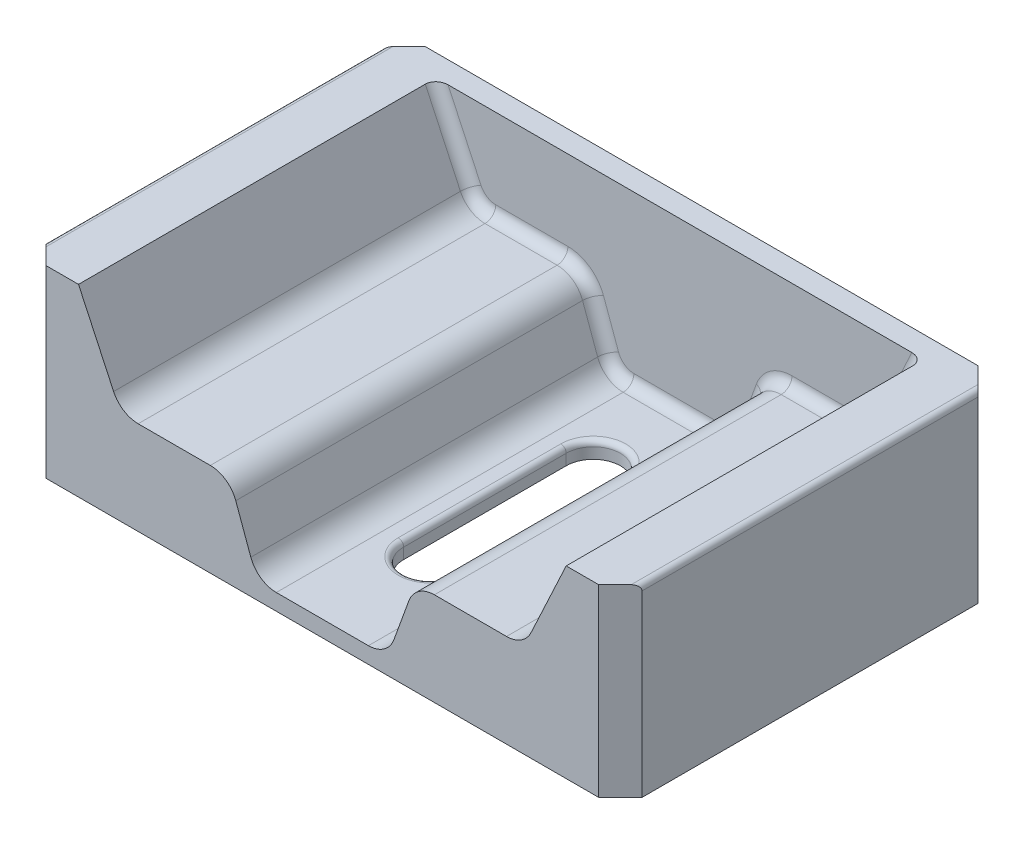
SolidWorks part; units mm, degrees
ref_plane "Front Plane" through (0, 0, 0) normal (0, 0, 1) x (1, 0, 0)
ref_plane "Top Plane" through (0, 0, 0) normal (0, 1, 0) x (1, 0, 0)
ref_plane "Right Plane" through (0, 0, 0) normal (1, 0, 0) x (0, 0, -1)
sketch "Sketch3" plane through (0, 0, 0) normal (0, 1, 0) x (1, 0, 0)
  line L1 (-69.85, -44.45) -> (69.85, -44.45)
  line L2 (-69.85, -44.45) -> (-69.85, 44.45)
  line L3 (-69.85, 44.45) -> (69.85, 44.45)
  line L4 (69.85, -44.45) -> (69.85, 44.45)
  line L5 (-69.85, -44.45) -> (69.85, 44.45) construction
  line L6 (-69.85, 44.45) -> (69.85, -44.45) construction
  point P0 (0, 0)
  dimension "D1" = 139.7
  dimension "D2" = 88.9
extrude "Boss-Extrude2" add sketch "Sketch3" along normal blind 43.18
sketch "Sketch4" plane through (0, 0, 44.45) normal (0, 0, 1) x (1, 0, 0)
  line L0 (-57.15, 43.18) -> (57.15, 43.18)
  line L1 (-69.85, 43.18) -> (69.85, 43.18) construction
  line L2 (57.15, 43.18) -> (47.2144, 21.8731)
  line L3 (47.2144, 21.8731) -> (21.8144, 21.8731)
  line L4 (21.8144, 21.8731) -> (15.24, 3.81)
  line L5 (15.24, 3.81) -> (-15.24, 3.81)
  line L6 (-15.24, 3.81) -> (-21.8144, 21.8731)
  line L7 (-21.8144, 21.8731) -> (-47.2144, 21.8731)
  line L8 (-47.2144, 21.8731) -> (-57.15, 43.18)
  line L9 (-69.85, 0) -> (69.85, 0) construction
  point P14 (0, 3.81)
  dimension "D1" = 114.3
  dimension "D2" = 30.48
  dimension "D3" = 25.4
  dimension "D4" = 25.4
  dimension "D5" = 110
  dimension "D6" = 110
  dimension "D7" = 115
  dimension "D8" = 115
  dimension "D9" = 3.81
extrude "Cut-Extrude1" cut sketch "Sketch4" against normal blind 83.82
sketch "Sketch6" plane through (0, 43.18, 0) normal (0, 1, 0) x (1, 0, 0)
  line L0 (0, -19.05) -> (0, 19.05) construction
  line L1 (-6.35, -19.05) -> (-6.35, 19.05)
  line L2 (6.35, -19.05) -> (6.35, 19.05)
  arc A0 (-6.35, -19.05) -> (6.35, -19.05) centre (0, -19.05) ccw
  arc A1 (6.35, 19.05) -> (-6.35, 19.05) centre (0, 19.05) ccw
  point P2 (0, 0)
  dimension "D2" = 6.35
  dimension "D1" = 38.1
extrude "Cut-Extrude2" cut sketch "Sketch6" against normal through all
chamfer "Chamfer1" distance 5.08 angle 45 4 edges at (-69.85, 21.59, -44.45) (69.85, 21.59, -44.45) (-69.85, 21.59, 44.45) (69.85, 21.59, 44.45)
fillet "Fillet1" radius 1.27 2 edges at (-69.85, 43.18, 0) (69.85, 43.18, 0)
fillet "Fillet2" radius 6.35 6 edges at (47.2144, 21.8731, 2.54) (21.8144, 21.8731, 2.54) (15.24, 3.81, 2.54) (-15.24, 3.81, 2.54) (-21.8144, 21.8731, 2.54) (-47.2144, 21.8731, 2.54)
fillet "Fillet3" radius 2.54 13 edges at (53.037, 34.3597, -39.37) (46.5809, 22.8676, -39.37) (34.7149, 21.8731, -39.37) (22.6185, 20.7247, -39.37) (18.5272, 12.8416, -39.37) (14.4359, 4.9584, -39.37) (0, 3.81, -39.37) (-14.4359, 4.9584, -39.37) (-18.5272, 12.8416, -39.37) (-22.6185, 20.7247, -39.37) (-34.7149, 21.8731, -39.37) (-46.5809, 22.8676, -39.37) (-53.037, 34.3597, -39.37)
fillet "Fillet4" radius 1.27 4 edges at (-6.35, 3.81, 0) (0, 3.81, 25.4) (6.35, 3.81, 0) (0, 3.81, -25.4)
